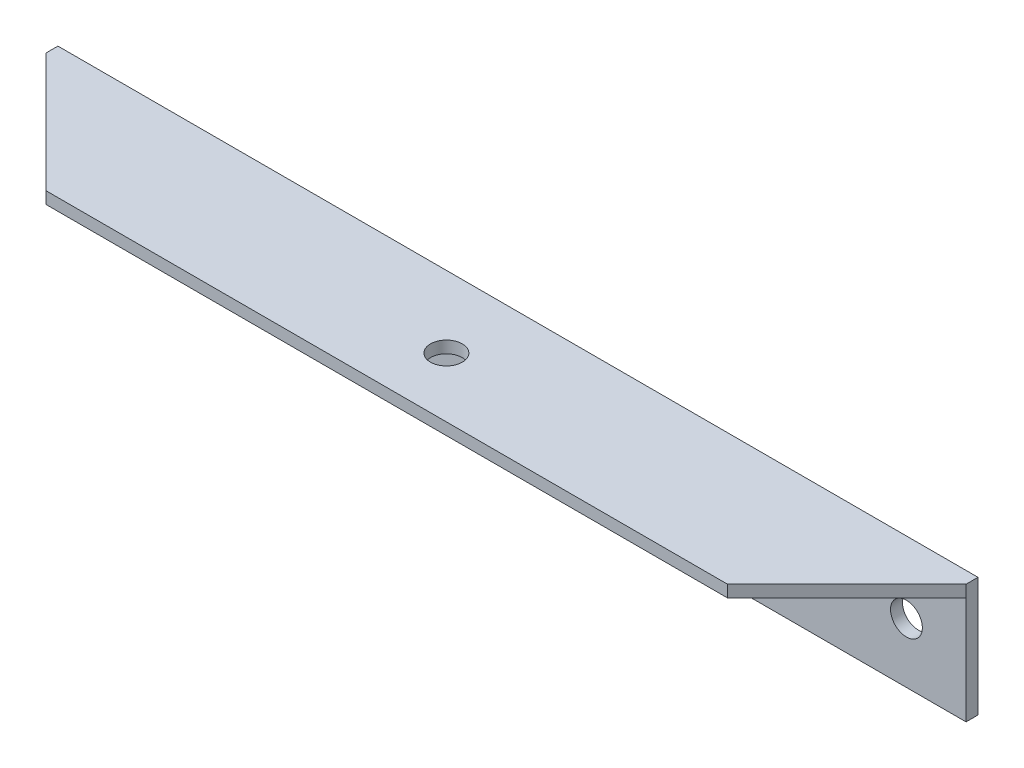
SolidWorks part; units mm, degrees
ref_plane "Front Plane" through (0, 0, 0) normal (0, 0, 1) x (1, 0, 0)
ref_plane "Top Plane" through (0, 0, 0) normal (0, 1, 0) x (1, 0, 0)
ref_plane "Right Plane" through (0, 0, 0) normal (1, 0, 0) x (0, 0, -1)
sketch "Sketch1" plane through (0, 0, 0) normal (0, 0, 1) x (1, 0, 0)
  line L0 (-115.7, 0) -> (115.7, 0)
  line L1 (-115.7, 0) -> (-115.7, -30)
  line L2 (115.7, 0) -> (115.7, -30)
  line L3 (-115.7, -30) -> (115.7, -30)
  point P4 (0, 0)
  dimension "D1" = 231.4
  dimension "D2" = 30
  dimension "D3" = 30
extrude "Boss-Extrude1" add sketch "Sketch1" along normal blind 3
sketch "Sketch3" plane through (0, 0, 0) normal (0, 1, 0) x (1, 0, 0)
  line L2 (-85.7, -33) -> (85.7, -33)
  line L3 (-115.7, -3) -> (115.7, -3)
  line L4 (-115.7, -3) -> (-85.7, -33)
  line L5 (115.7, -3) -> (85.7, -33)
  dimension "D1" = 30
  dimension "D3" = 45
  dimension "D4" = 45
extrude "Boss-Extrude2" add sketch "Sketch3" against normal blind 3
sketch "Sketch6" plane through (0, -3, 0) normal (0, -1, 0) x (1, 0, 0)
  line L2 (85.7, 33) -> (-85.7, 33) construction
  line L3 (0, 33) -> (0, 18) construction
  point P10 (0, 18)
  dimension "D1" = 15
sketch "Sketch7" plane through (0, 0, 0) normal (0, 0, -1) x (-1, 0, 0)
  line L0 (-115.7, -30) -> (-100.7, -30) construction
  line L1 (100.7, -15) -> (-100.7, -15) construction
  line L2 (-100.7, -15) -> (-100.7, -30) construction
  line L3 (115.7, 0) -> (115.7, -30) construction
  line L5 (115.7, -30) -> (100.7, -30) construction
  line L7 (100.7, -15) -> (100.7, -30) construction
  line L8 (115.7, -30) -> (-115.7, -30) construction
  point P5 (-100.7, -15)
  point P12 (100.7, -15)
  dimension "D1" = 15
  dimension "D2" = 15
  dimension "D3" = 216.4
  dimension "D4" = 15
  dimension "D5" = 15
  dimension "D6" = 30
  dimension "D7" = 30
hole_wizard "Ø8.0 (8) Diameter Hole1" positions "Sketch10" profile "Sketch11" hole size "Ø8.0" standard "AS" end condition through all
sketch "Sketch10" plane through (0, 0, 0) normal (0, 0, -1) x (-1, 0, 0)
  point P0 (100.7, -15)
  point P3 (-100.7, -15)
sketch "Sketch11" plane through (-100.7, -15, 0) normal (1, 0, 0) x (0, 1, 0)
  line L0 (0, 0) -> (0, 33)
  line L1 (0, 33) -> (4, 33)
  line L2 (4, 33) -> (4, 0)
  line L5 (4, 0) -> (0, 0)
  line L11 (0, -6.35) -> (0, 107.95) construction
  dimension "Thru Hole Dia." = 8
  dimension "Thru Hole Depth" = 33
hole_wizard "Ø8.0 (8) Diameter Hole2" positions "Sketch12" profile "Sketch13" hole size "Ø8.0" standard "AS" end condition through all
sketch "Sketch12" plane through (0, -3, 0) normal (0, -1, 0) x (-1, 0, 0)
  point P0 (0, -18)
sketch "Sketch13" plane through (0, -3, 18) normal (1, 0, 0) x (0, 0, -1)
  line L0 (0, 0) -> (0, 3)
  line L1 (0, 3) -> (4, 3)
  line L2 (4, 3) -> (4, 0)
  line L5 (4, 0) -> (0, 0)
  line L11 (0, -6.35) -> (0, 107.95) construction
  dimension "Thru Hole Dia." = 8
  dimension "Thru Hole Depth" = 3
